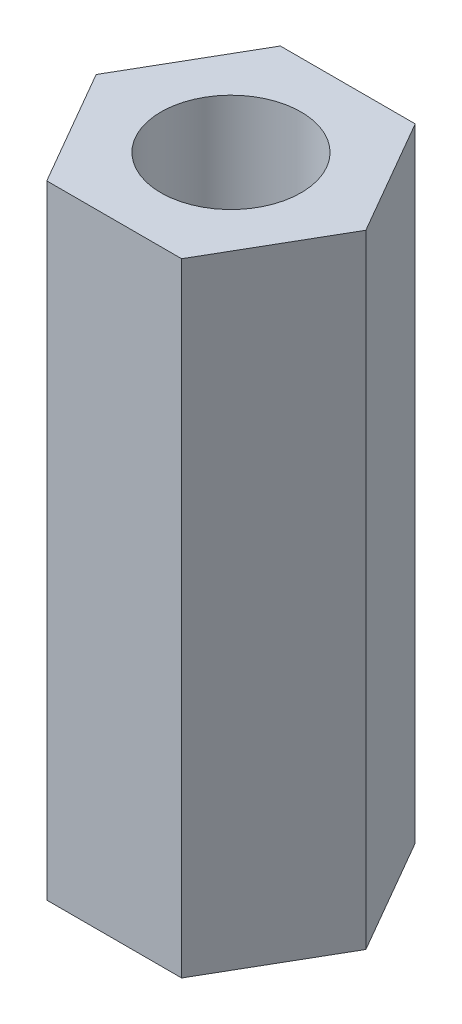
SolidWorks part; units mm, degrees
ref_plane "Front Plane" through (0, 0, 0) normal (0, 0, 1) x (1, 0, 0)
ref_plane "Top Plane" through (0, 0, 0) normal (0, 1, 0) x (1, 0, 0)
ref_plane "Right Plane" through (0, 0, 0) normal (1, 0, 0) x (0, 0, -1)
sketch "Sketch1" plane through (0, 0, 0) normal (0, 1, 0) x (1, 0, 0)
  line L1 (-1.299, -2.25) -> (1.299, -2.25)
  line L2 (1.299, -2.25) -> (2.5981, 0)
  line L3 (2.5981, 0) -> (1.299, 2.25)
  line L4 (1.299, 2.25) -> (-1.299, 2.25)
  line L5 (-1.299, 2.25) -> (-2.5981, 0)
  line L6 (-2.5981, 0) -> (-1.299, -2.25)
  circle A0 centre (0, 0) radius 2.25 construction
  dimension "D1" = 4.5
extrude "Boss-Extrude1" add sketch "Sketch1" along normal blind 12
sketch "Sketch2" plane through (0, 12, 0) normal (0, 1, 0) x (1, 0, 0)
  circle A0 centre (0, 0) radius 1.35
  dimension "D1" = 2.7
extrude "Cut-Extrude1" cut sketch "Sketch2" against normal through all
